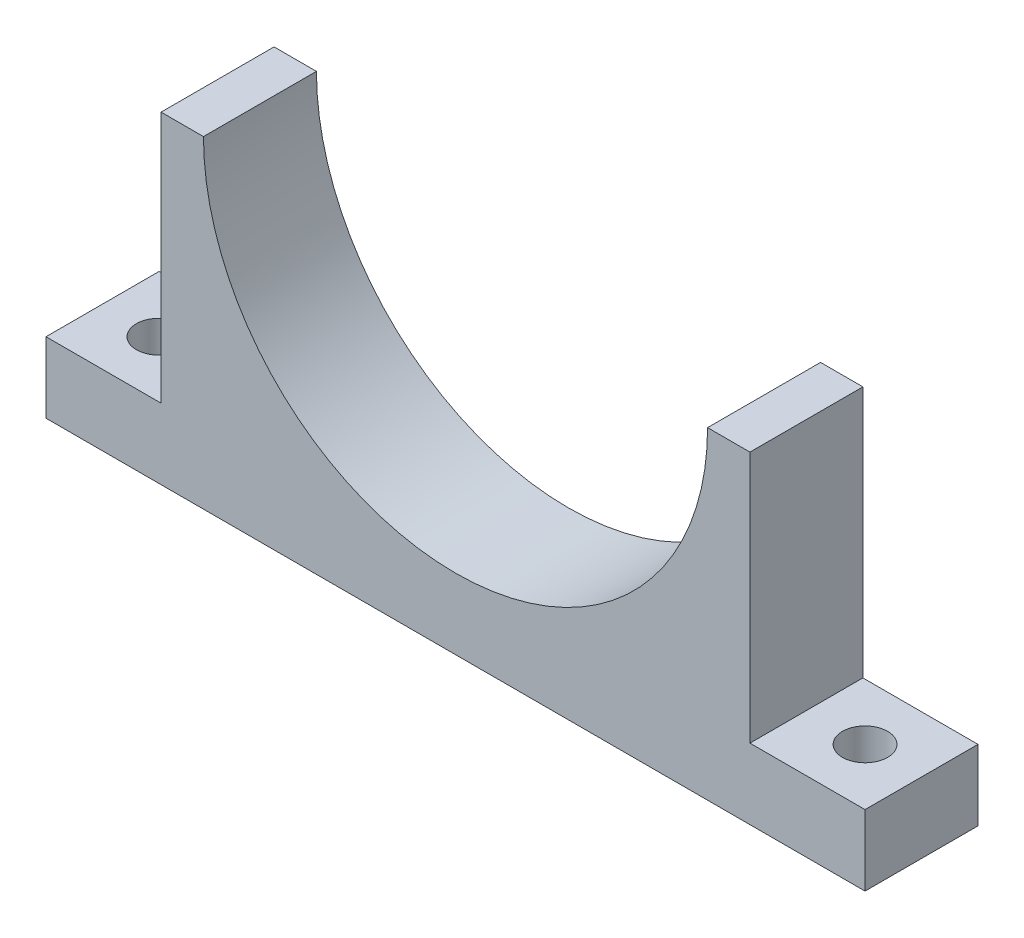
SolidWorks part; units mm, degrees
material "5052-O"
ref_plane "正面" through (0, 0, 0) normal (0, 0, 1) x (1, 0, 0)
ref_plane "平面" through (0, 0, 0) normal (0, 1, 0) x (1, 0, 0)
ref_plane "右側面" through (0, 0, 0) normal (1, 0, 0) x (0, 0, -1)
sketch "ｽｹｯﾁ1" plane through (0, 0, 0) normal (0, 0, 1) x (1, 0, 0)
  line L0 (-17.85, 0) -> (-20.85, 0)
  line L1 (-20.85, 0) -> (-20.85, -17.85)
  line L2 (-20.85, -17.85) -> (-29, -17.85)
  line L3 (-29, -17.85) -> (-29, -22.85)
  line L4 (-29, -22.85) -> (29, -22.85)
  line L5 (29, -22.85) -> (29, -17.85)
  line L6 (29, -17.85) -> (20.85, -17.85)
  line L7 (20.85, -17.85) -> (20.85, 0)
  line L8 (20.85, 0) -> (17.85, 0)
  arc A0 (-17.85, 0) -> (17.85, 0) centre (0, 0) ccw
  dimension "D1" = 17.85
  dimension "D2" = 3
  dimension "D3" = 5
  dimension "D4" = 8.15
extrude "ﾎﾞｽ - 押し出し1" add sketch "ｽｹｯﾁ1" along normal blind 8
sketch "ｽｹｯﾁ2" plane through (0, -22.85, 0) normal (0, -1, 0) x (1, 0, 0)
  line L0 (-29, 4) -> (29, 4) construction
  line L1 (-29, 8) -> (-29, 0) construction
  line L2 (29, 8) -> (29, 0) construction
  line L3 (0, 0) -> (0, 8) construction
  line L4 (-29, 8) -> (29, 8) construction
  circle A0 centre (-25, 4) radius 1.6
  circle A1 centre (25, 4) radius 1.6
  dimension "D1" = 3.2
  dimension "D2" = 4
extrude "ｶｯﾄ - 押し出し1" cut sketch "ｽｹｯﾁ2" against normal blind 8
